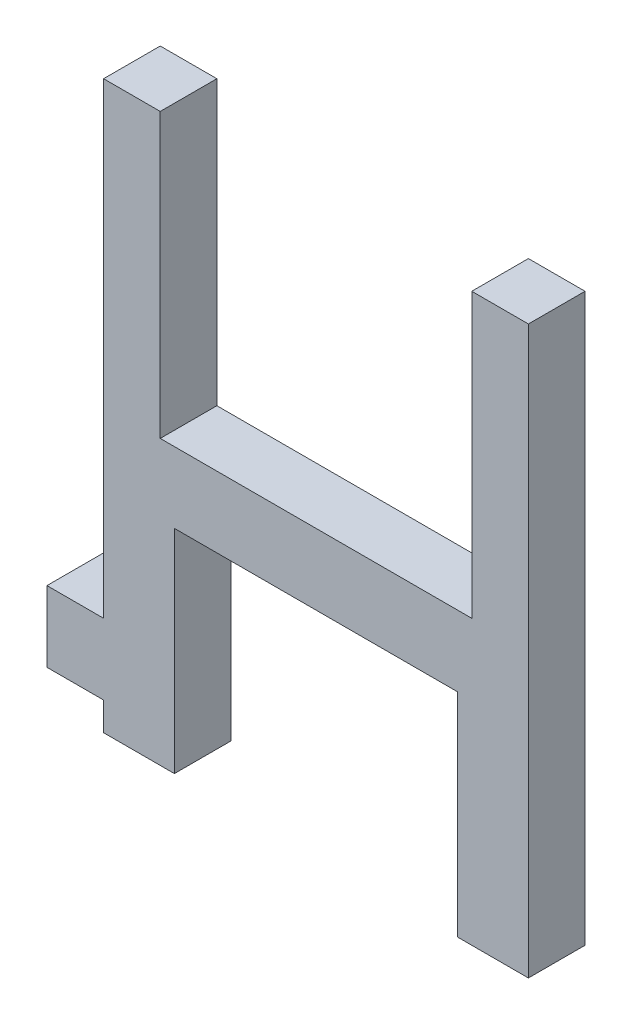
SolidWorks part; units mm, degrees
ref_plane "Přední rovina" through (0, 0, 0) normal (0, 0, 1) x (1, 0, 0)
ref_plane "Horní rovina" through (0, 0, 0) normal (0, 1, 0) x (1, 0, 0)
ref_plane "Pravá rovina" through (0, 0, 0) normal (1, 0, 0) x (0, 0, -1)
sketch "Skica1" plane through (0, 0, 0) normal (0, 0, 1) x (1, 0, 0)
  line L0 (0, 0) -> (5, 0)
  line L1 (5, 0) -> (5, -2)
  line L2 (5, -2) -> (10, -2)
  line L3 (10, -2) -> (10, 4.0825)
  line L4 (10, 4.0825) -> (10, 13)
  line L5 (10, 13) -> (30, 13)
  line L6 (30, 13) -> (30, -2)
  line L7 (30, -2) -> (35, -2)
  line L8 (35, -2) -> (35, 18)
  line L9 (35, 18) -> (5, 18)
  line L10 (5, 18) -> (5, 5)
  line L11 (5, 5) -> (0, 5)
  line L12 (0, 5) -> (0, 0)
  point P3 (2.5, 0)
  dimension "D1" = 5
  dimension "D2" = 20
  dimension "D3" = 5
  dimension "D4" = 15
  dimension "D5" = 5
  dimension "D6" = 6.0825
  dimension "D7" = 2
  dimension "D8" = 5
  dimension "D9" = 5
  dimension "D10" = 20
extrude "Přidat vysunutím1" add sketch "Skica1" along normal blind 4
sketch "Skica2" plane through (0, 18, 0) normal (0, 1, 0) x (1, 0, 0)
  line L0 (35, 0) -> (5, 0) construction
  line L1 (10, 0) -> (30, 0)
  line L2 (10, 0) -> (10, -4)
  line L3 (10, -4) -> (30, -4)
  line L4 (30, 0) -> (30, -4)
  line L5 (35, -4) -> (5, -4) construction
  line L6 (5, -4) -> (5, 0) construction
  line L7 (35, -4) -> (35, 0) construction
  dimension "D1" = 5
  dimension "D2" = 5
extrude "Přidat vysunutím2" add sketch "Skica2" along normal blind 15
sketch "Skica3" plane through (0, 0, 4) normal (0, 0, 1) x (1, 0, 0)
  line L1 (17.25, 29.5) -> (22.75, 29.5)
  line L2 (17.25, 29.5) -> (17.25, 26.5)
  line L3 (17.25, 26.5) -> (22.75, 26.5)
  line L4 (22.75, 29.5) -> (22.75, 26.5)
  line L6 (10, 18) -> (5, 18) construction
  line L7 (10, 33) -> (10, 18) construction
  point P6 (17.25, 28)
  dimension "D1" = 3
  dimension "D2" = 5.5
  dimension "D3" = 8.5
  dimension "D4" = 7.25
extrude "Odebrat vysunutím1" cut sketch "Skica3" against normal blind 15
sketch "Skica4" plane through (0, 0, 4) normal (0, 0, 1) x (1, 0, 0)
  line L1 (10, 33) -> (30, 33)
  line L2 (10, 33) -> (10, 18)
  line L3 (10, 18) -> (30, 18)
  line L4 (30, 33) -> (30, 18)
extrude "Odebrat vysunutím2" cut sketch "Skica4" against normal blind 15
sketch "Skica5" plane through (0, 18, 0) normal (0, 1, 0) x (1, 0, 0)
  line L1 (5, 0) -> (9, 0)
  line L2 (5, 0) -> (5, -4)
  line L3 (5, -4) -> (9, -4)
  line L4 (9, 0) -> (9, -4)
  line L5 (35, -4) -> (5, -4) construction
  line L7 (35, 0) -> (31, 0)
  line L8 (35, 0) -> (35, -4)
  line L9 (35, -4) -> (31, -4)
  line L10 (31, 0) -> (31, -4)
  dimension "D1" = 4
  dimension "D2" = 4
  dimension "D3" = 4
  dimension "D4" = 4
extrude "Přidat vysunutím3" add sketch "Skica5" along normal blind 20
sketch "Skica6" plane through (0, 0, 4) normal (0, 0, 1) x (1, 0, 0)
  line L0 (0, 0) -> (5, 0) construction
  line L1 (0, 5) -> (1, 5)
  line L2 (0, 5) -> (0, 0)
  line L3 (0, 0) -> (1, 0)
  line L4 (1, 5) -> (1, 0)
  dimension "D1" = 1
extrude "Odebrat vysunutím3" cut sketch "Skica6" against normal blind 10
